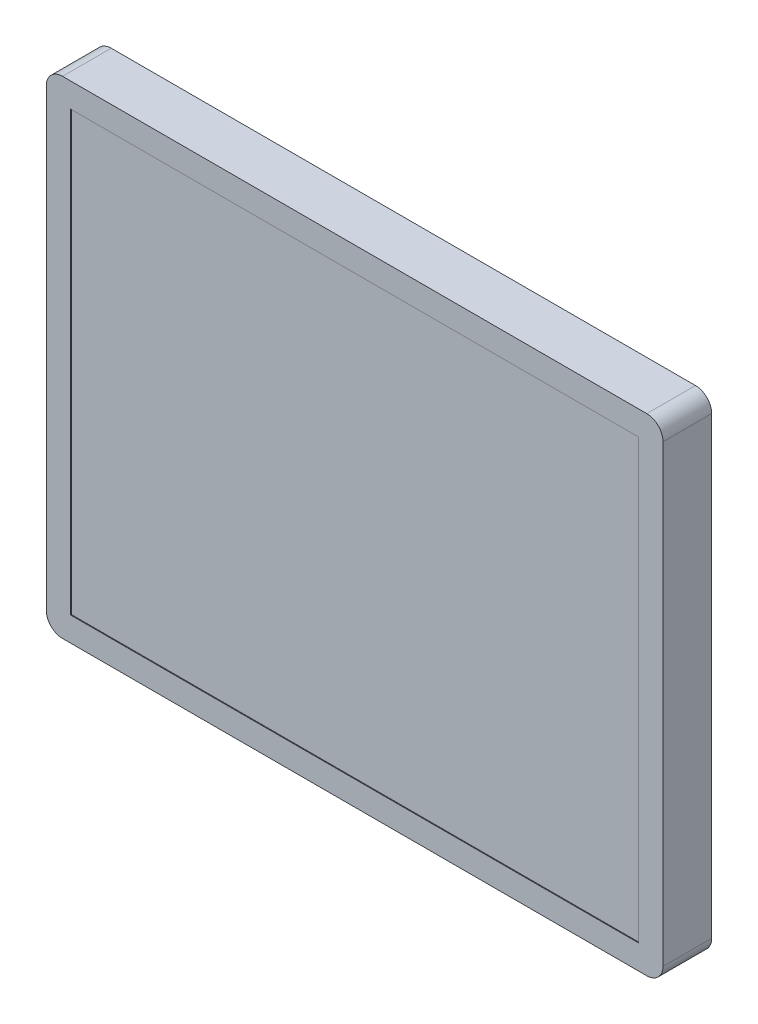
SolidWorks part; units mm, degrees
material "SKD11淬火HRC56－60"
ref_plane "前基準面" through (0, 0, 0) normal (0, 0, 1) x (1, 0, 0)
ref_plane "上基準面" through (0, 0, 0) normal (0, 1, 0) x (1, 0, 0)
ref_plane "右基準面" through (0, 0, 0) normal (1, 0, 0) x (0, 0, -1)
sketch "草图1" plane through (0, 0, 0) normal (0, 0, 1) x (1, 0, 0)
  line L1 (0, 0) -> (380, 0)
  line L2 (0, 0) -> (0, 300)
  line L3 (0, 300) -> (380, 300)
  line L4 (380, 0) -> (380, 300)
  dimension "D1" = 380
  dimension "D2" = 300
extrude "凸台-拉伸1" add sketch "草图1" along normal blind 30
sketch "草图2" plane through (0, 0, 30) normal (0, 0, 1) x (1, 0, 0)
  line L0 (0, 0) -> (380, 0) construction
  line L1 (15, 285) -> (365, 285)
  line L2 (15, 285) -> (15, 15)
  line L3 (15, 15) -> (365, 15)
  line L4 (365, 285) -> (365, 15)
  line L5 (380, 0) -> (380, 300) construction
  line L6 (380, 300) -> (0, 300) construction
  line L7 (0, 300) -> (0, 0) construction
  dimension "D1" = 15
  dimension "D2" = 15
  dimension "D3" = 15
  dimension "D4" = 15
extrude "切除-拉伸1" cut sketch "草图2" against normal blind 0.5
fillet "圆角1" radius 10 4 edges at (380, 0, 15) (0, 0, 15) (0, 300, 15) (380, 300, 15)
